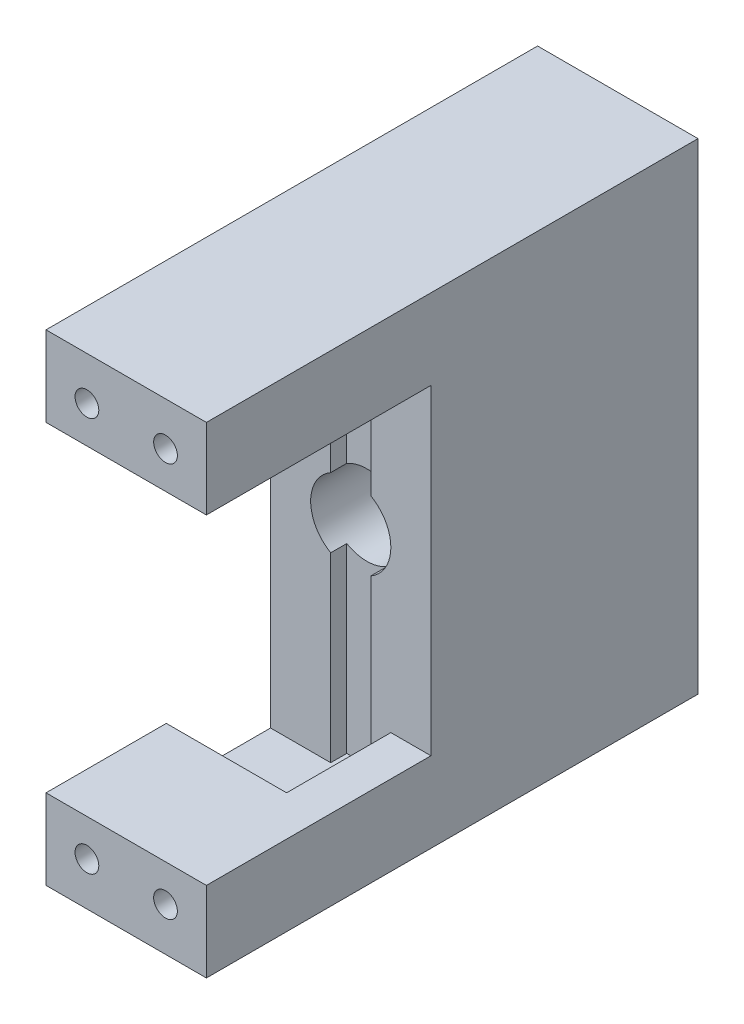
SolidWorks part; units mm, degrees
ref_plane "Front Plane" through (0, 0, 0) normal (0, 0, 1) x (1, 0, 0)
ref_plane "Top Plane" through (0, 0, 0) normal (0, 1, 0) x (1, 0, 0)
ref_plane "Right Plane" through (0, 0, 0) normal (1, 0, 0) x (0, 0, -1)
other "Configuration Table"
sketch "草图1" plane through (0, 0, 0) normal (0, 0, 1) x (1, 0, 0)
  line L0 (-15, 22) -> (-15, -22)
  line L1 (0, 22) -> (15, 22)
  line L2 (0, 22) -> (-15, 22)
  line L3 (15, 22) -> (15, -22)
  line L4 (15, -22) -> (-15, -22)
extrude "凸台-拉伸1" add sketch "草图1" along normal blind 14 contours L0 L4 L3 L1 L2
sketch "草图2" plane through (0, 22, 0) normal (0, 1, 0) x (1, 0, 0)
  line L3 (10, -4) -> (15, -14)
  line L4 (15, -14) -> (-15, -14)
  line L6 (-15, -14) -> (-10, -4)
  line L8 (3.1, -4) -> (3.1, 0)
  line L9 (-15, 0) -> (15, 0) construction
  line L10 (3.1, 0) -> (15, 0)
  line L11 (15, 0) -> (15, -14)
  line L12 (10, -4) -> (3.1, -4)
  line L13 (-3.1, -4) -> (-10, -4)
  line L14 (-15, -14) -> (-15, 0)
  line L15 (-15, 0) -> (-3.1, 0)
  line L16 (-3.1, 0) -> (-3.1, -4)
  line M14 (15, 0) -> (-15, 0)
  line M15 (-15, 0) -> (-15, -14)
  line M17 (15, -14) -> (15, 0)
extrude "切除-拉伸1" cut sketch "草图2" against normal blind 44 contours L16 L6 L13 M14 M15 | L12 L3 L8 M17 M14
sketch "草图3" plane through (0, 0, 0) normal (0, 0, -1) x (-1, 0, 0)
  line L2 (-3.1, 3.1) -> (-3.1, -3.1)
  line L4 (3.1, -22) -> (3.1, 22) construction
  line L5 (3.1, 3.1) -> (-3.1, 3.1)
  line L6 (-3.1, -22) -> (-3.1, 22) construction
  line L9 (-3.1, -3.1) -> (3.1, -3.1)
  line L10 (3.1, -22) -> (3.1, 22) construction
  line L11 (3.1, -3.1) -> (3.1, 3.1)
extrude "切除-拉伸2" cut sketch "草图3" against normal blind 4 contours L2 L9 L11 L5
sketch "草图4" plane through (0, 0, 14) normal (0, 0, 1) x (1, 0, 0)
  circle A0 centre (0, 0) radius 4
extrude "切除-拉伸3" cut sketch "草图4" against normal blind 5
sketch "草图5" plane through (0, 0, 9) normal (0, 0, 1) x (1, 0, 0)
  circle A0 centre (0, 0) radius 2.6
extrude "切除-拉伸4" cut sketch "草图5" against normal blind 5 contours A0
sketch "草图6" plane through (0, -22, 0) normal (0, -1, 0) x (1, 0, 0)
  line L0 (-10, 4) -> (-15, 14)
  line L1 (-10, 4) -> (-10, 14)
  line L2 (15, 14) -> (-15, 14) construction
  line L3 (-10, 14) -> (-15, 14)
  line L4 (10, 4) -> (10, 14)
  line L5 (10, 14) -> (15, 14)
  line L6 (15, 14) -> (10, 4)
extrude "切除-拉伸5" cut sketch "草图6" against normal blind 50 contours L3 L0 L1 | L6 L4 L5
sketch "草图8" plane through (0, -22, 0) normal (0, -1, 0) x (-1, 0, 0)
  line L0 (10, -14) -> (-10, -14)
  line L1 (-10, -14) -> (-10, -4)
  line L2 (-10, -4) -> (-3.1, -4)
  line L3 (-3.1, -4) -> (-3.1, 0)
  line L4 (-3.1, 0) -> (3.1, 0)
  line L5 (3.1, 0) -> (3.1, -4)
  line L6 (3.1, -4) -> (10, -4)
  line L7 (10, -4) -> (10, -14)
extrude "凸台-拉伸2" add sketch "草图8" along normal blind 8 contours L7 L0 L1 L2 L3 L4 L5 L6
sketch "草图9" plane through (0, 22, 0) normal (0, 1, 0) x (1, 0, 0)
  line L0 (-3.1, -4) -> (-3.1, 0)
  line L1 (-10, -14) -> (10, -14)
  line L2 (-10, -14) -> (-10, -4)
  line L4 (10, -14) -> (10, -4)
  line L9 (-3.1, 0) -> (3.1, 0)
  line L10 (3.1, 0) -> (3.1, -4)
  line L11 (-10, -4) -> (-3.1, -4)
  line L12 (3.1, -4) -> (10, -4)
extrude "凸台-拉伸3" add sketch "草图9" along normal blind 8
sketch "草图10" plane through (0, 0, 14) normal (0, 0, 1) x (1, 0, 0)
  line L0 (10, 30) -> (10, -30) construction
  line L1 (-10, 30) -> (10, 30)
  line L2 (-10, 30) -> (-10, 20)
  line L3 (-10, 20) -> (10, 20)
  line L4 (10, 30) -> (10, 20)
  line L6 (-10, -30) -> (10, -30)
  line L7 (-10, -30) -> (-10, -20)
  line L8 (-10, -20) -> (10, -20)
  line L9 (10, -30) -> (10, -20)
extrude "凸台-拉伸4" add sketch "草图10" along normal blind 18 contours L8 L2 L1 L3
sketch "草图12" plane through (0, 0, 32) normal (0, 0, 1) x (1, 0, 0)
  line L0 (0, 0) -> (0, 24.6)
  line L1 (0, 0) -> (0, -24.6)
  line L2 (0, 24.6) -> (4.9, 24.6)
  line L3 (0, 24.6) -> (-4.9, 24.6)
  line L4 (0, -24.6) -> (4.9, -24.6)
  line L5 (0, -24.6) -> (-4.9, -24.6)
  circle A0 centre (-4.9, -24.6) radius 1.48
  circle A1 centre (4.9, -24.6) radius 1.48
  circle A2 centre (-4.9, 24.6) radius 1.48
  circle A3 centre (4.9, 24.6) radius 1.48
extrude "切除-拉伸6" cut sketch "草图12" against normal blind 20
sketch "草图13" plane through (10, 0, 0) normal (1, 0, 0) x (0, 0, -1)
  line L1 (-14, 20) -> (-10, 20)
  line L2 (-14, 20) -> (-14, -20)
  line L3 (-14, -20) -> (-10, -20)
  line L4 (-10, 20) -> (-10, -20)
extrude "切除-拉伸7" cut sketch "草图13" against normal blind 22
sketch "草图16" plane through (0, 0, 10) normal (0, 0, 1) x (1, 0, 0)
  circle A0 centre (0, 0) radius 5
extrude "切除-拉伸8" cut sketch "草图16" against normal blind 3
sketch "草图17" plane through (0, 0, 10) normal (0, 0, 1) x (1, 0, 0)
  line L0 (0, -20) -> (0, -15)
  line L1 (-10, 20) -> (10, 20) construction
  line L2 (0, 20) -> (0, 15)
  line L3 (-10, -20) -> (10, -20) construction
  circle A0 centre (0, 15) radius 5
  circle A1 centre (0, -15) radius 5
extrude "切除-拉伸9" cut sketch "草图17" against normal blind 3
sketch "草图18" plane through (0, 0, 7) normal (0, 0, 1) x (1, 0, 0)
  circle A0 centre (0, 15) radius 2.6
  circle A1 centre (0, -15) radius 2.6
extrude "切除-拉伸10" cut sketch "草图18" against normal blind 99 contours A1 | A0
sketch "草图19" plane through (0, 0, 10) normal (0, 0, 1) x (1, 0, 0)
  circle A0 centre (0, 0) radius 5
extrude "凸台-拉伸5" add sketch "草图19" against normal blind 6 contours A0
sketch "草图20" plane through (0, 0, 0) normal (0, 0, -1) x (-1, 0, 0)
  line L0 (0, 15) -> (0, 18.1)
  line L1 (0, 18.1) -> (3.1, 18.1)
  line L2 (3.1, 3.1) -> (3.1, 30) construction
  line L3 (0, 15) -> (0, 11.9)
  line L4 (0, 11.9) -> (-3.1, 11.9)
  line L5 (-3.1, 3.1) -> (-3.1, 30) construction
  line L6 (0, -15) -> (0, -11.9)
  line L7 (-3.1, 11.9) -> (3.1, 11.9)
  line L8 (-3.1, 11.9) -> (-3.1, 18.1)
  line L9 (-3.1, 18.1) -> (3.1, 18.1)
  line L10 (3.1, 11.9) -> (3.1, 18.1)
  line L11 (0, -11.9) -> (3.1, -11.9)
  line L12 (3.1, -30) -> (3.1, -3.1) construction
  line L13 (0, -15) -> (0, -18.1)
  line L14 (0, -18.1) -> (-3.1, -18.1)
  line L15 (-3.1, -30) -> (-3.1, -3.1) construction
  line L17 (-3.1, -18.1) -> (3.1, -18.1)
  line L18 (-3.1, -18.1) -> (-3.1, -11.9)
  line L19 (-3.1, -11.9) -> (3.1, -11.9)
  line L20 (3.1, -18.1) -> (3.1, -11.9)
extrude "切除-拉伸11" cut sketch "草图20" against normal blind 4 contours L17 L20 L11 L6 L13 | L19 L18 L14 L13 L6 | L8 L7 L10 L9
sketch "草图21" plane through (0, 0, 0) normal (0, 0, -1) x (-1, 0, 0)
  line L1 (-3.1, 3.1) -> (3.1, 3.1)
  line L2 (-3.1, 3.1) -> (-3.1, -3.1)
  line L3 (-3.1, -3.1) -> (3.1, -3.1)
  line L4 (3.1, 3.1) -> (3.1, -3.1)
extrude "凸台-拉伸6" add sketch "草图21" against normal blind 4 contours L2 L1 L4 L3
sketch "草图22" plane through (0, 0, 0) normal (0, 0, -1) x (-1, 0, 0)
  line L0 (-3.1, 30) -> (3.1, 30) construction
  line L1 (-3.1, -30) -> (-3.05, -30)
  line L2 (-3.1, -30) -> (-3.1, 30)
  line L3 (-3.1, 30) -> (-3.05, 30)
  line L4 (-3.05, -30) -> (-3.05, 30)
  line L5 (-3.1, -30) -> (3.1, -30) construction
  line L6 (3.1, 30) -> (3.05, 30)
  line L7 (3.1, 30) -> (3.1, -30)
  line L8 (3.1, -30) -> (3.05, -30)
  line L9 (3.05, 30) -> (3.05, -30)
extrude "切除-拉伸12" cut sketch "草图22" against normal blind 4
sketch "草图25" plane through (0, 0, 32) normal (0, 0, 1) x (1, 0, 0)
  line L0 (-10, -30) -> (10, -30) construction
  line L1 (-10, 20) -> (10, 20)
  line L2 (-10, 20) -> (-10, 30)
  line L3 (-10, 30) -> (10, 30)
  line L4 (10, 20) -> (10, 30)
  line L5 (-10, -20) -> (10, -20)
  line L6 (-10, -20) -> (-10, -30)
  line L7 (-10, -30) -> (10, -30)
  line L8 (10, -20) -> (10, -30)
  line L9 (10, -30) -> (10, -20) construction
  circle A0 centre (-4.9, -24.6) radius 1.48
  circle A1 centre (4.9, -24.6) radius 1.48
  circle A2 centre (-4.9, 24.6) radius 1.48
  circle A3 centre (4.9, 24.6) radius 1.48
extrude "凸台-拉伸7" add sketch "草图25" along normal blind 6 contours L8 L5 L6 L7 A1 A0 | L2 L1 L4 L3
sketch "草图27" plane through (0, -20, 0) normal (0, 1, 0) x (1, 0, 0)
  line L0 (10, -10) -> (4, -10)
  line L1 (0, -10) -> (10, -10) construction
  line L2 (4, -10) -> (4, -15)
  line L3 (4, -15) -> (-4, -15)
  line L4 (-4, -15) -> (-4, -10)
  line L5 (-10, -10) -> (0, -10) construction
  line L6 (-4, -10) -> (4, -10)
  line M7 (10, -10) -> (0, -10)
  line M8 (0, -10) -> (-10, -10)
extrude "切除-拉伸13" cut sketch "草图27" against normal blind 7 contours L4 L3 L2 M7 M8
sketch "草图28" plane through (-10, 0, 0) normal (-1, 0, 0) x (0, 0, 1)
  line L0 (4, 30) -> (38, 30) construction
  line L1 (10, 20) -> (18, 20)
  line L2 (10, 20) -> (10, 30)
  line L3 (10, 30) -> (18, 30)
  line L4 (18, 20) -> (18, 30)
  line L5 (4, -30) -> (38, -30) construction
  line L6 (10, -20) -> (18, -20)
  line L7 (10, -20) -> (10, -30)
  line L8 (10, -30) -> (18, -30)
  line L9 (18, -20) -> (18, -30)
  line M14 (4, -30) -> (38, -30)
  line M16 (38, -20) -> (10, -20)
extrude "凸台-拉伸8" add sketch "草图28" against normal blind 20 contours L9 L7 M16 M14 | L2 L1 L4 L3
sketch "草图29" plane through (0, -20, 0) normal (0, 1, 0) x (1, 0, 0)
  line L0 (10, -10) -> (4, -10)
  line L1 (0, -10) -> (10, -10) construction
  line L2 (4, -10) -> (4, -20)
  line L3 (4, -20) -> (-4, -20)
  line L4 (-4, -20) -> (-4, -10)
  line L5 (-10, -10) -> (0, -10) construction
  line L6 (-4, -10) -> (4, -10)
  line M6 (10, -10) -> (0, -10)
  line M7 (0, -10) -> (-10, -10)
extrude "切除-拉伸14" cut sketch "草图29" against normal blind 7 contours L4 L3 L2 M6 M7
sketch "草图30" plane through (0, -20, 0) normal (0, 1, 0) x (1, 0, 0)
  line L0 (-10, -38) -> (-10, -10) construction
  line L1 (-4, -20) -> (-10, -20)
  line L2 (-4, -20) -> (-4, -17.0173)
  line L3 (-4, -17.0173) -> (-10, -17.0173)
  line L4 (-10, -20) -> (-10, -17.0173)
  line L5 (10, -38) -> (10, -10) construction
  line L6 (4, -20) -> (10, -20)
  line L7 (4, -20) -> (4, -16.7349)
  line L8 (4, -16.7349) -> (10, -16.7349)
  line L9 (10, -20) -> (10, -16.7349)
extrude "凸台-拉伸9" add sketch "草图30" against normal blind 7
sketch "草图31" plane through (0, -20, 0) normal (0, 1, 0) x (1, 0, 0)
  line L0 (10, -38) -> (10, -10) construction
  line L1 (4, -20) -> (10, -20)
  line L2 (4, -20) -> (4, -22)
  line L3 (4, -22) -> (10, -22)
  line L4 (10, -20) -> (10, -22)
  line L5 (-10, -38) -> (-10, -10) construction
  line L6 (4, -20) -> (-10, -20)
  line L7 (4, -20) -> (4, -22)
  line L8 (4, -22) -> (-10, -22)
  line L9 (-10, -20) -> (-10, -22)
  line M6 (10, -38) -> (10, -10)
  line M9 (4, -20) -> (-4, -20)
  line M12 (-10, -10) -> (-10, -38)
extrude "凸台-拉伸10" add sketch "草图31" against normal blind 10 contours L2 L3 L1 M6 | L8 L2 L6 M9 M12
sketch "草图32" plane through (0, 0, 0) normal (0, 0, -1) x (-1, 0, 0)
  line L0 (-3.05, -30) -> (-3.05, -27)
  line L1 (-3.05, -30) -> (-3.05, -18.1) construction
  line L2 (3.05, -18.1) -> (3.05, -30) construction
  line L3 (-3.05, -27) -> (3.05, -27)
  line L4 (-3.05, -27) -> (-3.05, -24)
  line L5 (-3.05, -24) -> (3.05, -24)
  line L6 (3.05, -27) -> (3.05, -24)
  line M7 (-3.05, -18.1) -> (-3.05, -30)
  line M9 (3.05, -30) -> (3.05, -18.1)
extrude "切除-拉伸15" cut sketch "草图32" against normal blind 10 contours L5 L3 M7 M9
sketch "草图33" plane through (0, 0, 0) normal (0, 0, -1) x (-1, 0, 0)
  line L1 (-3.05, -27) -> (3.05, -27)
  line L2 (-3.05, -27) -> (-3.05, -30)
  line L3 (-3.05, -30) -> (3.05, -30)
  line L4 (3.05, -27) -> (3.05, -30)
extrude "切除-拉伸16" cut sketch "草图33" against normal blind 4 contours L2 L1 L4 L3
sketch "草图34" plane through (-10, 0, 0) normal (-1, 0, 0) x (0, 0, 1)
  line L1 (10, -20) -> (20, -20)
  line L2 (10, -20) -> (10, -25)
  line L3 (10, -25) -> (20, -25)
  line L4 (20, -20) -> (20, -25)
extrude "切除-拉伸17" cut sketch "草图34" against normal blind 6 contours L2 L1 L4 L3
sketch "草图35" plane through (-10, 0, 0) normal (-1, 0, 0) x (0, 0, 1)
  line L1 (20, -20) -> (21, -20)
  line L2 (20, -20) -> (20, -25)
  line L3 (20, -25) -> (21, -25)
  line L4 (21, -20) -> (21, -25)
extrude "切除-拉伸18" cut sketch "草图35" against normal blind 14
sketch "草图36" plane through (-10, 0, 0) normal (-1, 0, 0) x (0, 0, 1)
  line L0 (10, -20) -> (21, -20) construction
  line L1 (10, -25) -> (16, -25)
  line L2 (10, -25) -> (10, -20)
  line L3 (10, -20) -> (16, -20)
  line L4 (16, -25) -> (16, -20)
extrude "凸台-拉伸11" add sketch "草图36" against normal blind 6 contours L2 L1 L4 L3
sketch "草图37" plane through (0, -25, 0) normal (0, 1, 0) x (1, 0, 0)
  line L0 (4, -21) -> (-10, -21) construction
  line L1 (4, -20) -> (-4, -20)
  line L2 (4, -20) -> (4, -21)
  line L3 (4, -21) -> (-4, -21)
  line L4 (-4, -20) -> (-4, -21)
extrude "切除-拉伸19" cut sketch "草图37" against normal blind 2
sketch "草图38" plane through (0, 0, 10) normal (0, 0, 1) x (1, 0, 0)
  circle A0 centre (0, 15) radius 5
  circle A1 centre (0, -15) radius 5
extrude "凸台-拉伸12" add sketch "草图38" against normal blind 6
sketch "草图39" plane through (0, 0, 10) normal (0, 0, 1) x (1, 0, 0)
  circle A0 centre (0, 0) radius 2.6
extrude "切除-拉伸20" cut sketch "草图39" against normal blind 10
sketch "草图40" plane through (0, 0, 10) normal (0, 0, 1) x (1, 0, 0)
  circle A0 centre (0, 0) radius 5
extrude "切除-拉伸21" cut sketch "草图40" against normal blind 3
sketch "草图41" plane through (0, 0, 10) normal (0, 0, 1) x (1, 0, 0)
  line L1 (-10, 20) -> (10, 20)
  line L2 (-10, 20) -> (-10, -20)
  line L3 (-10, -20) -> (10, -20)
  line L4 (10, 20) -> (10, -20)
  circle A0 centre (0, 0) radius 5
extrude "凸台-拉伸13" add sketch "草图41" along normal blind 1 contours L2 L1 L4 L3 | A0
sketch "草图42" plane through (0, 0, 38) normal (0, 0, 1) x (1, 0, 0)
  line L1 (-10, 30) -> (10, 30)
  line L2 (-10, 30) -> (-10, 20)
  line L3 (-10, 20) -> (10, 20)
  line L4 (10, 30) -> (10, 20)
  line L5 (-10, -20) -> (10, -20)
  line L6 (-10, -20) -> (-10, -30)
  line L7 (-10, -30) -> (10, -30)
  line L8 (10, -20) -> (10, -30)
  circle A0 centre (-4.9, 24.6) radius 1.48
  circle A1 centre (4.9, 24.6) radius 1.48
  circle A2 centre (-4.9, -24.6) radius 1.48
  circle A3 centre (4.9, -24.6) radius 1.48
extrude "凸台-拉伸14" add sketch "草图42" along normal blind 1
sketch "草图43" plane through (-10, 0, 0) normal (-1, 0, 0) x (0, 0, 1)
  line L0 (39, -20) -> (24, -20)
  line L1 (39, -20) -> (21, -20) construction
  line L3 (24, -20) -> (10.9977, -20)
  line L4 (24, -20) -> (24, -27)
  line L5 (24, -27) -> (10.9977, -27)
  line L6 (10.9977, -20) -> (10.9977, -27)
  line M6 (16, -20) -> (11, -20)
  line M14 (39, -20) -> (21, -20)
  line M15 (21, -20) -> (21, -25)
  line M16 (21, -25) -> (16, -25)
  line M17 (16, -25) -> (16, -20)
extrude "切除-拉伸22" cut sketch "草图43" against normal blind 15 contours L3 L6 L5 L4 M14 M15 M16 M17 M6 | L3 M15 M17 M16
sketch "草图44" plane through (0, 0, 24) normal (0, 0, -1) x (-1, 0, 0)
  line L0 (-5, -23.1234) -> (-5, -26.0766)
  circle A0 centre (-4.9, -24.6) radius 1.48
extrude "凸台-拉伸15" add sketch "草图44" along normal blind 2 contours L0 A0
sketch "草图45" plane through (0, 0, 0) normal (0, 0, -1) x (-1, 0, 0)
  line L0 (-10, -30) -> (10, -30) construction
  line L1 (-3.05, -11.9) -> (3.05, -11.9)
  line L2 (-3.05, -11.9) -> (-3.05, -30)
  line L3 (-3.05, -30) -> (3.05, -30)
  line L4 (3.05, -11.9) -> (3.05, -30)
  line L6 (-3.05, 11.9) -> (3.05, 11.9)
  line L7 (-3.05, 11.9) -> (-3.05, 30)
  line L8 (-3.05, 30) -> (3.05, 30)
  line L9 (3.05, 11.9) -> (3.05, 30)
extrude "凸台-拉伸16" add sketch "草图45" against normal blind 10
sketch "草图46" plane through (0, 0, 0) normal (0, 0, -1) x (-1, 0, 0)
  line L0 (0, 0) -> (0, 3.05)
  line L1 (0, 3.05) -> (3.05, 3.05)
  line L2 (3.05, 30) -> (3.05, -30) construction
  line L3 (0, 0) -> (0, -3.05)
  line L4 (0, -3.05) -> (-3.05, -3.05)
  line L5 (-3.05, -30) -> (-3.05, 30) construction
  line L7 (-3.05, -3.05) -> (3.05, -3.05)
  line L8 (-3.05, -3.05) -> (-3.05, 3.05)
  line L9 (-3.05, 3.05) -> (3.05, 3.05)
  line L10 (3.05, -3.05) -> (3.05, 3.05)
  circle M7 centre (0, 0) radius 2.6
  line M8 (3.05, -30) -> (3.05, 30)
  line M10 (-3.05, 30) -> (-3.05, -30)
extrude "切除-拉伸23" cut sketch "草图46" against normal blind 4 contours L0 L3 M7 | L3 L0 M7 | L9 L4 L3 L0 M10 M7 | L3 L7 L1 L0 M8 M7
sketch "草图47" plane through (0, 0, 11) normal (0, 0, 1) x (1, 0, 0)
  line L0 (5, -20) -> (-10, -20)
  line L1 (-10, -20) -> (-10, -27.0024)
  line L2 (-10, -27.0024) -> (5, -27.0024)
  line L3 (5, -27.0024) -> (5, -20)
extrude "凸台-拉伸17" add sketch "草图47" against normal blind 4
sketch "草图48" plane through (0, 0, 11) normal (0, 0, 1) x (1, 0, 0)
  line L4 (-10, -27) -> (5, -27) construction
  line L5 (0, -27) -> (2.5, -27)
  line L6 (2.5, 0) -> (2.5, 20)
  line L8 (-2.5, 0) -> (-2.5, -27)
  line L9 (-2.5, -27) -> (2.5, -27)
  line L10 (2.5, 0) -> (2.5, -27)
  line L11 (-10, 20) -> (10, 20) construction
  line L12 (2.5, 20) -> (-2.5, 20)
  line L13 (-2.5, 20) -> (-2.5, -27)
  line L14 (2.5, -27) -> (2.5, 20)
  line M8 (-10, -27) -> (5, -27)
  line M12 (10, 20) -> (-10, 20)
  circle M13 centre (0, 0) radius 5
extrude "切除-拉伸24" cut sketch "草图48" against normal blind 1 contours L13 L6 M12 M13 | L10 L8 M13 M8
sketch "草图49" plane through (-10, 0, 0) normal (-1, 0, 0) x (0, 0, 1)
  line L0 (11, 20) -> (9, 20)
  line L4 (2, 30) -> (9, 20)
  line L6 (4, 30) -> (0, 30) construction
  line L7 (4, 30) -> (11, 20)
  line L10 (4, 30) -> (4, 31.5466)
  line L11 (4, 31.5466) -> (2, 31.5466)
  line L12 (2, 30) -> (2, 31.5466)
  line L13 (11, 20) -> (9, 20)
  line L14 (11, 20) -> (11, 19)
  line L15 (11, 19) -> (9, 19)
  line L16 (9, 20) -> (9, 19)
  line M8 (11, -27) -> (11, 20)
  line M12 (4, 30) -> (4, -30)
extrude "切除-拉伸27" cut sketch "草图49" against normal blind 12.5 contours L0 L16 L15 M8 | L7 L4 L0 M12 | L12 L4 L10 L11 M12
sketch "草图51" plane through (0, 19, 0) normal (0, 1, 0) x (1, 0, 0)
  line L0 (2.5, -10) -> (-2.5, -10)
  line L1 (-2.5, -10) -> (-2.5, -9)
  line L2 (2.5, -9) -> (-10, -9) construction
  line L3 (-2.5, -9) -> (2.5, -9)
  line L4 (2.5, -9) -> (2.5, -10)
extrude "凸台-拉伸18" add sketch "草图51" along normal blind 1
sketch "草图52" plane through (-2.5, 0, 0) normal (-1, 0, 0) x (0, 0, 1)
  line L0 (9, 20) -> (10, 19)
  line L1 (10, 19) -> (10, 20)
  line L2 (10, 20) -> (9, 20)
extrude "切除-拉伸28" cut sketch "草图52" against normal blind 5
sketch "草图53" plane through (-10, 0, 0) normal (-1, 0, 0) x (0, 0, 1)
  line L0 (11, 20) -> (4, 30)
  line L2 (11, 20) -> (11, 19)
  line L3 (11, 19) -> (9, 19)
  line L4 (9, 20) -> (9, 19)
  line L5 (4, 30) -> (2, 30)
  line L6 (2, 30) -> (9, 20)
extrude "凸台-拉伸19" add sketch "草图53" against normal blind 7.5 contours L0 L5 L6 L4 L3 L2
sketch "草图54" plane through (0, 30, 0) normal (0, 1, 0) x (1, 0, 0)
  line L0 (2.5, -4) -> (3.05, -4)
  line L2 (-3.05, -2) -> (-2.5, -2)
  line L3 (-3.05, -2) -> (-3.05, -4)
  line L4 (-3.05, -4) -> (-2.5, -4)
  line L5 (-2.5, -2) -> (-2.5, -4)
  line L6 (-3.05, -4) -> (-10, -4)
  line L7 (-3.05, -4) -> (-3.05, -2)
  line L8 (-3.05, -2) -> (-10, -2)
  line L9 (-10, -4) -> (-10, -2)
  line M2 (-3.05, -2) -> (-10, -2)
  line M3 (-10, -2) -> (-10, -39)
extrude "切除-拉伸29" cut sketch "草图54" against normal blind 7.5 contours L6 L3 M2 M3
sketch "草图55" plane through (0, 0, 0) normal (0, 0, -1) x (-1, 0, 0)
  line L0 (3.05, 30) -> (3.05, 3.05) construction
  line L1 (-3.05, 30) -> (3.05, 30)
  line L2 (-3.05, 30) -> (-3.05, 27)
  line L3 (-3.05, 27) -> (3.05, 27)
  line L4 (3.05, 30) -> (3.05, 27)
extrude "切除-拉伸30" cut sketch "草图55" against normal blind 4
sketch "草图56" plane through (0, 0, 4) normal (0, 0, -1) x (-1, 0, 0)
  line L1 (-2.5, 27.1429) -> (3.05, 27.1429)
  line L2 (-2.5, 27.1429) -> (-2.5, 27)
  line L3 (-2.5, 27) -> (3.05, 27)
  line L4 (3.05, 27.1429) -> (3.05, 27)
  line L5 (-2.5, 27.1429) -> (-3.05, 27.1429)
  line L6 (-2.5, 27.1429) -> (-2.5, 27)
  line L7 (-2.5, 27) -> (-3.05, 27)
  line L8 (-3.05, 27.1429) -> (-3.05, 27)
  line M8 (-3.05, 27) -> (3.05, 27)
  line M13 (2.5, 27.1429) -> (-2.5, 27.1429)
extrude "凸台-拉伸20" add sketch "草图56" along normal blind 4 contours L5 L8 L2 M8 | L4 L1 L2 M13 M8
sketch "草图60" plane through (-10, 0, 0) normal (-1, 0, 0) x (0, 0, 1)
  line L0 (11, 20) -> (11, 30)
  line L1 (4, 30) -> (39, 30) construction
  line L3 (11, 30) -> (-22.3, 30)
  line L4 (11, 30) -> (11, -30)
  line L5 (11, -30) -> (-22.3, -30)
  line L6 (-22.3, 30) -> (-22.3, -30)
  line M5 (39, 30) -> (4, 30)
  line M6 (4, 30) -> (4, -30)
  line M7 (4, -30) -> (39, -30)
  line M12 (11, -27) -> (11, 20)
extrude "凸台-拉伸21" add sketch "草图60" against normal blind 20 contours L3 L6 L5 M6 | L4 L0 M12 M5 M6 M7
sketch "草图61" plane through (0, 0, -22.3) normal (0, 0, -1) x (-1, 0, 0)
  line L0 (0, 0) -> (0, 30)
  line L1 (-10, 30) -> (10, 30) construction
  line L2 (0, 0) -> (0, -30)
  line L3 (-10, -30) -> (10, -30) construction
  line L4 (0, -30) -> (3.05, -30)
  line L5 (0, 30) -> (-3.05, 30)
  line L7 (-3.05, 30) -> (3.05, 30)
  line L8 (-3.05, 30) -> (-3.05, -30)
  line L9 (-3.05, -30) -> (3.05, -30)
  line L10 (3.05, 30) -> (3.05, -30)
  line M4 (10, 30) -> (-10, 30)
  line M6 (-10, -30) -> (10, -30)
extrude "凸台-拉伸22" add sketch "草图61" along normal blind 4 contours L8 L2 L0 M4 M6 | L10 L0 L2 M4 M6
sketch "草图62" plane through (0, 0, 11) normal (0, 0, 1) x (1, 0, 0)
  circle A0 centre (0, 0) radius 2.6
extrude "切除-拉伸31" cut sketch "草图62" against normal blind 50
sketch "草图63" plane through (0, 0, 11) normal (0, 0, 1) x (1, 0, 0)
  circle A0 centre (0, 0) radius 5
extrude "切除-拉伸32" cut sketch "草图63" against normal blind 30.3
sketch "草图64" plane through (0, 0, -26.3) normal (0, 0, -1) x (-1, 0, 0)
  line L0 (0, 0) -> (0, 3.05)
  line L1 (0, 3.05) -> (-3.05, 3.05)
  line L2 (-3.05, 30) -> (-3.05, -30) construction
  line L3 (0, 0) -> (0, -3.05)
  line L4 (0, -3.05) -> (3.05, -3.05)
  line L5 (3.05, 30) -> (3.05, -30) construction
  line L7 (-3.05, 3.05) -> (3.05, 3.05)
  line L8 (-3.05, 3.05) -> (-3.05, -3.05)
  line L9 (-3.05, -3.05) -> (3.05, -3.05)
  line L10 (3.05, 3.05) -> (3.05, -3.05)
  circle M7 centre (0, 0) radius 2.6
  line M9 (-3.05, 30) -> (-3.05, -30)
  line M11 (3.05, -30) -> (3.05, 30)
extrude "切除-拉伸33" cut sketch "草图64" against normal blind 4 contours L7 L0 L3 L4 M7 M11 | L9 L3 L0 L1 M9 M7
sketch "草图65" plane through (0, 0, 11) normal (0, 0, 1) x (1, 0, 0)
  line L0 (0, 0) -> (0, 20)
  line L1 (-10, 20) -> (10, 20) construction
  line L2 (0, 20) -> (2.5, 20)
  line L3 (0, 0) -> (0, -27)
  line L4 (-10, -27) -> (5, -27) construction
  line L5 (0, -27) -> (-2.5, -27)
  line L7 (2.5, 20) -> (-2.5, 20)
  line L8 (2.5, 20) -> (2.5, -27)
  line L9 (2.5, -27) -> (-2.5, -27)
  line L10 (-2.5, 20) -> (-2.5, -27)
  circle M2 centre (0, 0) radius 5
  line M4 (10, 20) -> (-10, 20)
  line M6 (-10, -27) -> (5, -27)
extrude "切除-拉伸34" cut sketch "草图65" against normal blind 2 contours L8 L0 M4 M2 | L10 L0 M4 M2 | L8 L3 M2 M6 | L10 L3 M2 M6
sketch "草图66" plane through (0, 0, 9) normal (0, 0, 1) x (1, 0, 0)
  line L0 (2.5, 20) -> (2.5, 4.3301) construction
  line L1 (-2.5, 20) -> (2.5, 20)
  line L2 (-2.5, 20) -> (-2.5, 18)
  line L3 (-2.5, 18) -> (2.5, 18)
  line L4 (2.5, 20) -> (2.5, 18)
extrude "切除-拉伸35" cut sketch "草图66" against normal blind 50
sketch "草图67" plane through (0, 0, -26.3) normal (0, 0, -1) x (-1, 0, 0)
  line L0 (2.5, 18) -> (3.05, 18)
  line L1 (3.05, 30) -> (3.05, 3.05) construction
  line L3 (-3.05, 30) -> (3.05, 30)
  line L4 (-3.05, 30) -> (-3.05, 18)
  line L5 (-3.05, 18) -> (3.05, 18)
  line L6 (3.05, 30) -> (3.05, 18)
  line M1 (2.5, 20) -> (2.5, 18)
  line M3 (-2.5, 18) -> (-2.5, 20)
  line M4 (-2.5, 20) -> (2.5, 20)
  line M5 (-3.05, 30) -> (-3.05, 3.05)
  line M7 (3.05, 3.05) -> (3.05, 30)
  line M8 (3.05, 30) -> (-3.05, 30)
extrude "切除-拉伸36" cut sketch "草图67" against normal blind 4 contours L5 L0 M5 M3 M4 M1 M7 M8
sketch "草图68" plane through (0, 0, 9) normal (0, 0, 1) x (1, 0, 0)
  line L0 (2.5, 20) -> (2.5, 4.3301) construction
  line L1 (-2.5, 18) -> (2.5, 18)
  line L2 (-2.5, 18) -> (-2.5, 16)
  line L3 (-2.5, 16) -> (2.5, 16)
  line L4 (2.5, 18) -> (2.5, 16)
extrude "切除-拉伸37" cut sketch "草图68" against normal blind 2 contours L2 L1 L4 L3
